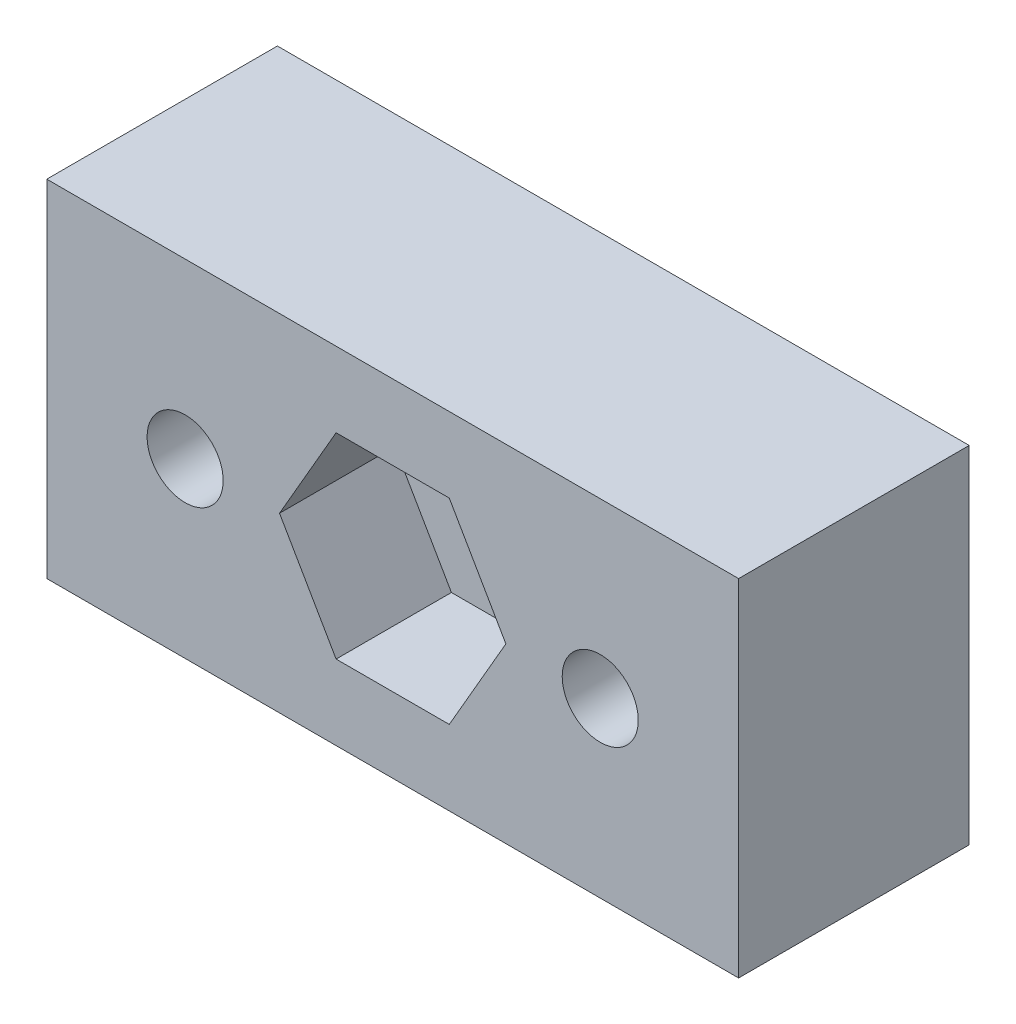
SolidWorks part; units mm, degrees
ref_plane "Front Plane" through (0, 0, 0) normal (0, 0, 1) x (1, 0, 0)
ref_plane "Top Plane" through (0, 0, 0) normal (0, 1, 0) x (1, 0, 0)
ref_plane "Right Plane" through (0, 0, 0) normal (1, 0, 0) x (0, 0, -1)
sketch "Sketch3" plane through (0, 0, 0) normal (0, 0, 1) x (1, 0, 0)
  line L1 (-30, -15) -> (30, -15)
  line L2 (-30, -15) -> (-30, 15)
  line L3 (-30, 15) -> (30, 15)
  line L4 (30, -15) -> (30, 15)
  point P7 (0, -15)
  point P8 (-30, 0)
  dimension "D1" = 60
  dimension "D2" = 30
extrude "Boss-Extrude1" add sketch "Sketch3" along normal mid plane 20
sketch "Sketch7" plane through (0, 0, -10) normal (0, 0, -1) x (-1, 0, 0)
  line L0 (0, 0) -> (0, 23.1499) construction
  point P0 (18, 0)
  point P2 (-18, 0)
  dimension "D1" = 18
hole_wizard "CBORE for M6 Hex Head Cap Screw1" positions "Sketch7" profile "Sketch6" counterbore size "M6" standard "ISO" end condition through all
sketch "Sketch6" plane through (-18, 0, -10) normal (1, 0, 0) x (0, 1, 0)
  line L0 (0, 0) -> (0, 20)
  line L1 (0, 20) -> (3.3, 20)
  line L3 (3.3, 20) -> (3.3, 7.5)
  line L4 (3.3, 7.5) -> (5.25, 7.5)
  line L5 (5.25, 7.5) -> (5.25, 0)
  line L7 (5.25, 0) -> (0, 0)
  line L11 (0, -6.35) -> (0, 107.95) construction
  dimension "Thru Hole Dia." = 6.6
  dimension "Thru Hole Depth" = 20
  dimension "C'Bore Dia." = 10.5
  dimension "C'Bore Depth" = 7.5
sketch "Sketch10" plane through (0, 0, -10) normal (0, 0, -1) x (-1, 0, 0)
  point P0 (0, 0)
hole_wizard "Tap Drill for M12 Tap1" positions "Sketch10" profile "Sketch9" hole size "M12" standard "ISO" end condition through all
sketch "Sketch9" plane through (0, 0, -10) normal (1, 0, 0) x (0, 1, 0)
  line L0 (0, 0) -> (0, 20)
  line L1 (0, 20) -> (5.125, 20)
  line L2 (5.1, 19.975) -> (5.1, 0.025)
  line L3 (5.1, 0.025) -> (5.125, 0)
  line L5 (5.125, 0) -> (0, 0)
  line L6 (-5.1, 0.025) -> (-5.125, 0) construction
  line L7 (5.125, 20) -> (5.1, 19.975)
  line L8 (-5.125, 20) -> (-5.1, 19.975) construction
  line L11 (0, -6.35) -> (0, 107.95) construction
  dimension "Thru Hole Dia." = 10.2
  dimension "Thru Hole Depth" = 20
  dimension "Near C'Sink Dia." = 10.25
  dimension "Near C'Sink Angle" = 90
  dimension "Far C'Sink Dia." = 10.25
  dimension "Far C'Sink Angle" = 90
sketch "Sketch11" plane through (0, 0, 10) normal (0, 0, -1) x (-1, 0, 0)
  line L0 (-30, 15) -> (30, 15) construction
  line L1 (4.9075, 8.5) -> (-4.9075, 8.5)
  line L2 (-4.9075, 8.5) -> (-9.815, 0)
  line L3 (-9.815, 0) -> (-4.9075, -8.5)
  line L4 (-4.9075, -8.5) -> (4.9075, -8.5)
  line L5 (4.9075, -8.5) -> (9.815, 0)
  line L6 (9.815, 0) -> (4.9075, 8.5)
  circle A0 centre (0, 0) radius 8.5 construction
  dimension "D1" = 17
extrude "Cut-Extrude1" cut sketch "Sketch11" along normal blind 10
mirror "Mirror1" [suppressed] about plane through (0, 0, 0) normal (0, 0, 1)
